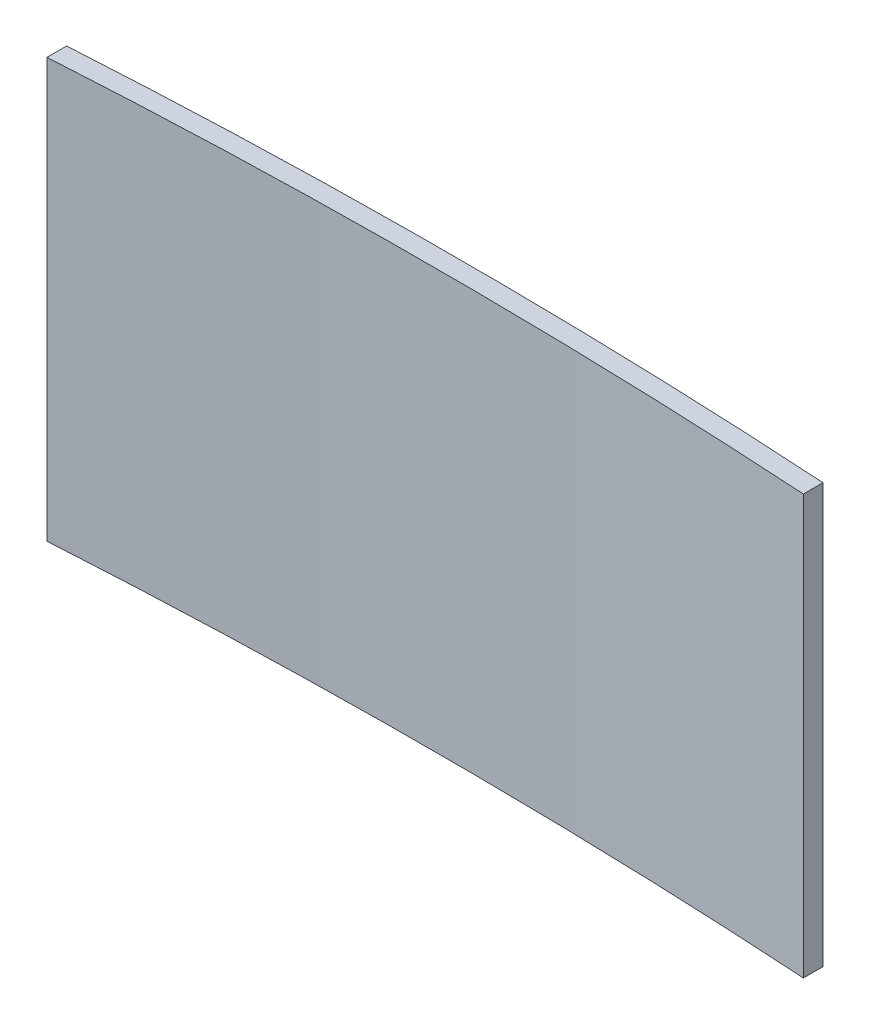
SolidWorks part; units mm, degrees
ref_plane "Front Plane" through (0, 0, 0) normal (0, 0, 1) x (1, 0, 0)
ref_plane "Top Plane" through (0, 0, 0) normal (0, 1, 0) x (1, 0, 0)
ref_plane "Right Plane" through (0, 0, 0) normal (1, 0, 0) x (0, 0, -1)
sketch "Sketch3" plane through (0, 0, 0) normal (0, 1, 0) x (1, 0, 0)
  line L0 (0, 0) -> (0, 12.7244)
  line L2 (490.5356, 12.7244) -> (490.5356, 0)
  spline S0 degree 2 poles (0, 0) (245.2678, 15.24) (490.5356, 0) knots 0 0 0 1 1 1
  spline S1 degree 1 poles (-0.7876, 12.6756) (491.3232, 12.6756) knots 0 0 1 1 construction
  spline S2 degree 3 poles (-0.7876, 12.6756) (19.7076, 13.949) (60.7298, 16.1795) (142.7418, 19.3643) (245.2678, 20.9571) (347.7938, 19.3643) (429.8058, 16.1795) (470.828, 13.949) (491.3232, 12.6756) knots 0 0 0 0 0.125 0.25 0.5 0.75 0.875 1 1 1 1 only from (0, 12.7244) to (490.5356, 12.7244)
  dimension "D1" = 12.7
extrude "Boss-Extrude1" add sketch "Sketch3" along normal blind 271.78
ref_plane "Plane1" through (0, 0, -8.89) normal (0, 0, 1) x (1, 0, 0)
sketch "Sketch4" plane through (0, 0, -8.89) normal (0, 0, 1) x (1, 0, 0)
  line L0 (0, 271.78) -> (0, 239.268) construction
  line L1 (0, 271.78) -> (0, 0) construction
  line L2 (0, 239.268) -> (6.35, 239.268) construction
  line L3 (6.35, 239.268) -> (6.35, 226.568)
  line L4 (6.35, 226.568) -> (19.05, 226.568)
  line L5 (19.05, 226.568) -> (19.05, 239.268)
  line L6 (19.05, 239.268) -> (6.35, 239.268)
  line L7 (238.9178, 271.78) -> (238.9178, 137.7427) construction
  line L8 (477.8356, 271.78) -> (0, 271.78) construction
  line L9 (458.7856, 239.268) -> (471.4856, 239.268)
  line L10 (458.7856, 226.568) -> (458.7856, 239.268)
  line L11 (471.4856, 226.568) -> (458.7856, 226.568)
  line L12 (471.4856, 239.268) -> (471.4856, 226.568)
extrude "Boss-Extrude2" add sketch "Sketch4" against normal blind 7.62
sketch "Sketch5" plane through (0, 271.78, 0) normal (0, 1, 0) x (1, 0, 0)
  line L0 (486.1356, 12.9945) -> (486.1356, 38.9532)
  line L1 (486.1356, 38.9532) -> (439.0744, 31.9404)
  line L2 (439.0744, 31.9404) -> (441.5308, 15.4564)
  spline S0 degree 3 poles (179.5968, -1506.7587) (2812.8348, -626.8236) (1593.823, -29.0229) (347.7938, 19.3643) (245.2678, 20.9571) (142.7418, 19.3643) (-1103.283, -29.0228) (-2322.2902, -626.8191) (310.9091, -1506.7488) knots -7.096628 -7.096628 -7.096628 -7.096628 0.125 0.25 0.5 0.75 0.875 8.096601 8.096601 8.096601 8.096601 only from (490.5356, 12.7244) to (0, 12.7244) construction
  spline S1 degree 3 poles (486.1356, 12.9945) (471.2722, 13.8986) (456.4014, 14.7193) (441.5308, 15.4564) knots 0.010546 0.010546 0.010546 0.010546 0.101186 0.101186 0.101186 0.101186
extrude "Cut-Extrude1" cut sketch "Sketch5" against normal through all
ref_plane "Plane2" through (245.2678, 0, 0) normal (-1, 0, 0) x (0, 0, 1)
mirror "Mirror2" about plane through (245.2678, 0, 0) normal (-1, 0, 0) of "Boss-Extrude2"
sketch "Sketch6" plane through (0, 271.78, 0) normal (0, 1, 0) x (1, 0, 0)
  line L1 (19.05, 13.8585) -> (19.05, 29.4179)
  line L2 (19.05, 29.4179) -> (39.0109, 22.949)
  line L3 (39.0109, 22.949) -> (39.4256, 14.97)
  spline S0 degree 3 poles (179.5968, -1506.7587) (2812.8348, -626.8236) (1593.823, -29.0229) (347.7938, 19.3643) (245.2678, 20.9571) (142.7418, 19.3643) (-1103.283, -29.0228) (-2322.2902, -626.8191) (310.9091, -1506.7488) knots -7.096628 -7.096628 -7.096628 -7.096628 0.125 0.25 0.5 0.75 0.875 8.096601 8.096601 8.096601 8.096601 only from (490.5356, 12.7244) to (0, 12.7244) construction
  spline S1 degree 3 poles (39.4256, 14.97) (32.6332, 14.617) (25.8411, 14.2464) (19.05, 13.8585) knots 0.918277 0.918277 0.918277 0.918277 0.959679 0.959679 0.959679 0.959679
extrude "Cut-Extrude2" cut sketch "Sketch6" against normal through all
